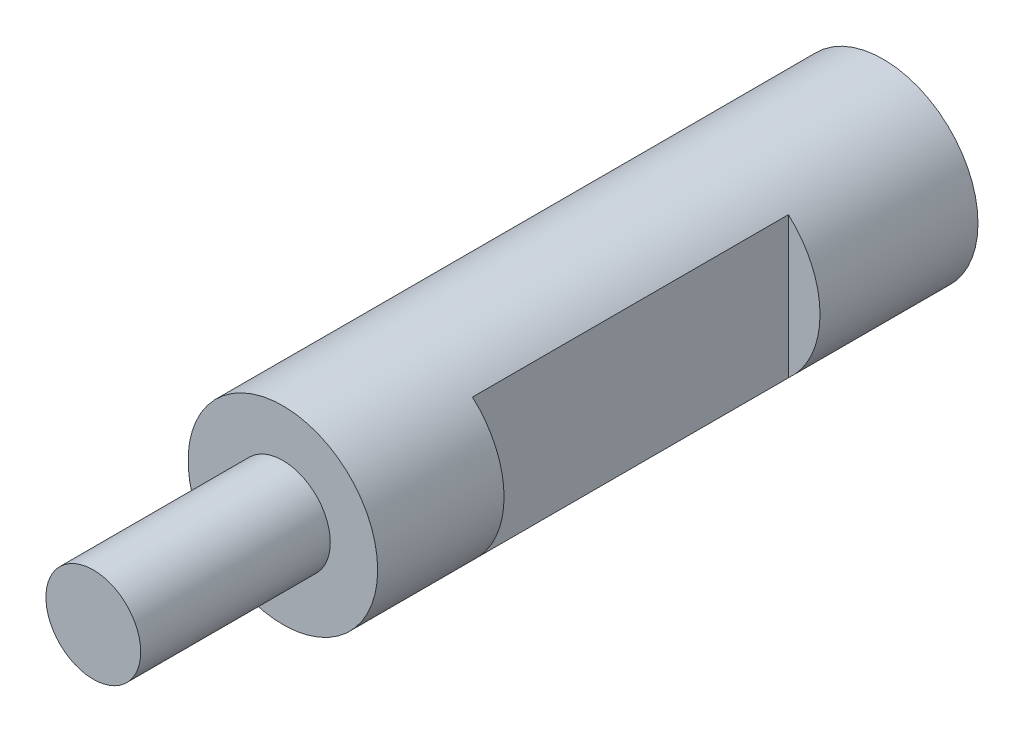
SolidWorks part; units mm, degrees
ref_plane "前视基准面" through (0, 0, 0) normal (0, 0, 1) x (1, 0, 0)
ref_plane "上视基准面" through (0, 0, 0) normal (0, 1, 0) x (1, 0, 0)
ref_plane "右视基准面" through (0, 0, 0) normal (1, 0, 0) x (0, 0, -1)
sketch "草图1" plane through (0, 0, 0) normal (0, 0, 1) x (1, 0, 0)
  circle A0 centre (0, 0) radius 3
extrude "拉伸1" add sketch "草图1" along normal blind 19
sketch "草图2" plane through (0, 0, 0) normal (0, 1, 0) x (1, 0, 0)
  line L0 (-3, 0) -> (-3, -19) construction
  line L1 (-3, -5) -> (-2, -5)
  line L2 (-3, -5) -> (-3, -15)
  line L3 (-3, -15) -> (-2, -15)
  line L4 (-2, -5) -> (-2, -15)
  line L5 (3, -19) -> (3, 0) construction
  line L6 (3, -5) -> (2, -5)
  line L7 (3, -5) -> (3, -15)
  line L8 (3, -15) -> (2, -15)
  line L9 (2, -5) -> (2, -15)
  line L10 (3, 0) -> (-3, 0) construction
  dimension "D1" = 10
  dimension "D2" = 10
  dimension "D3" = 4
  dimension "D4" = 1
  dimension "D5" = 5
  dimension "D6" = 5
extrude "拉伸2" cut sketch "草图2" against normal mid plane 18.5
hole_wizard "M3 螺纹孔1" positions "3D草图1" profile "草图3" tap size "M3" standard "GB"
sketch3d "3D草图1"
  point P1 (0, 0, 0)
sketch "草图3" plane through (0, 0, 0) normal (1, 0, 0) x (0, 1, 0)
  line L0 (0, 0) -> (0, 8.2511)
  line L1 (0, 8.2511) -> (1.25, 7.5)
  line L2 (1.25, 7.5) -> (1.25, 6)
  line L3 (1.25, 6) -> (1.5, 6)
  line L4 (1.5, 6) -> (1.5, 0)
  line L5 (1.5, 0) -> (0, 0)
  line L10 (0, 8.2511) -> (-1.25, 7.5) construction
  line L11 (0, -6.35) -> (0, 107.95) construction
  dimension "螺纹孔钻头直径" = 2.5
  dimension "螺纹孔钻头深度" = 7.5
  dimension "螺纹主直径" = 3
  dimension "螺纹深度" = 6
  dimension "导头角度" = 118
sketch "草图4" plane through (0, 0, 19) normal (0, 0, 1) x (1, 0, 0)
  circle A0 centre (0, 0) radius 1.5
extrude "拉伸3" add sketch "草图4" along normal blind 6
cosmetic thread "装饰螺纹线1" parameters "D1"=5, "D2"=2.25
